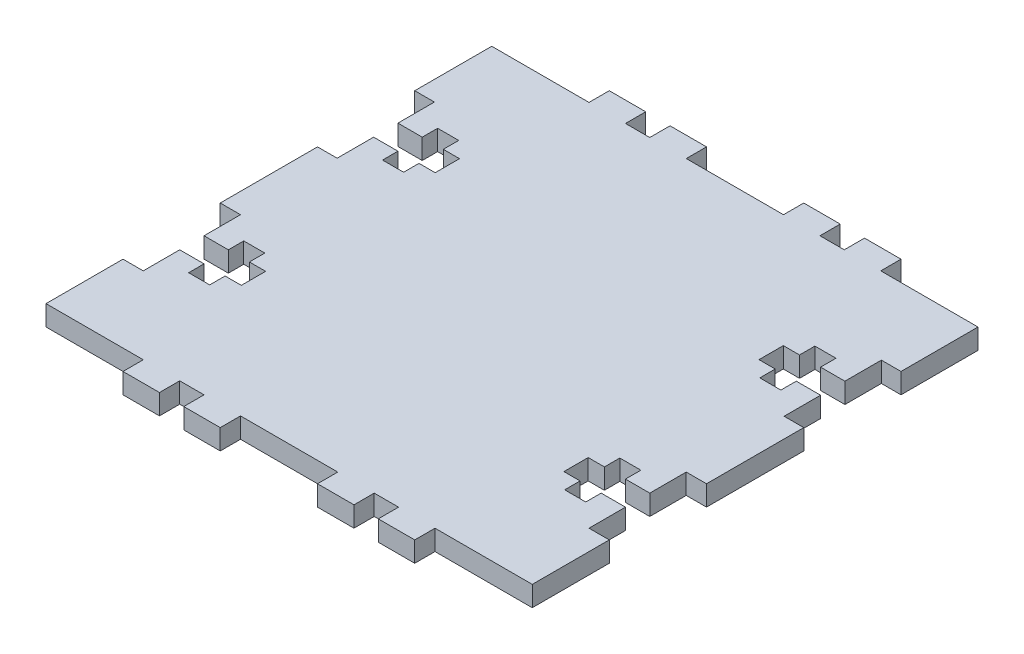
SolidWorks part; units mm, degrees
ref_plane "Front Plane" through (0, 0, 0) normal (0, 0, 1) x (1, 0, 0)
ref_plane "Top Plane" through (0, 0, 0) normal (0, 1, 0) x (1, 0, 0)
ref_plane "Right Plane" through (0, 0, 0) normal (1, 0, 0) x (0, 0, -1)
sketch "Sketch1" plane through (0, 0, 0) normal (0, 1, 0) x (1, 0, 0)
  line L0 (-38.1, 38.1) -> (38.1, -38.1) construction
  line L1 (-38.1, 38.1) -> (38.1, 38.1) construction
  line L2 (-38.1, 38.1) -> (-38.1, -38.1) construction
  line L3 (-38.1, -38.1) -> (38.1, -38.1) construction
  line L4 (38.1, 38.1) -> (38.1, -38.1) construction
  line L5 (15.24, 38.1) -> (15.24, 36.5125) construction
  line L6 (34.925, 34.925) -> (34.925, -34.925) construction
  line L7 (-34.925, -34.925) -> (34.925, -34.925) construction
  line L8 (-27.813, -13.335) -> (-25.273, -13.335)
  line L9 (-22.86, 36.5125) -> (-7.62, 36.5125) construction
  line L10 (-34.925, 34.925) -> (-22.86, 34.925)
  line L11 (-22.86, 34.925) -> (-22.86, 38.1)
  line L12 (-22.86, 38.1) -> (-17.145, 38.1)
  line L13 (-7.62, 38.1) -> (-7.62, 34.925)
  line L14 (-7.62, 34.925) -> (7.62, 34.925)
  line L15 (7.62, 34.925) -> (7.62, 38.1)
  line L16 (13.335, 38.1) -> (7.62, 38.1)
  line L17 (22.86, 38.1) -> (22.86, 34.925)
  line L18 (22.86, 34.925) -> (34.925, 34.925)
  line L19 (7.62, 36.5125) -> (22.86, 36.5125) construction
  line L20 (-15.24, -38.1) -> (-15.24, -36.5125) construction
  line L21 (-15.24, 38.1) -> (-15.24, 36.5125) construction
  line L22 (7.62, -36.5125) -> (22.86, -36.5125) construction
  line L23 (-22.86, -36.5125) -> (-7.62, -36.5125) construction
  line L24 (15.24, -38.1) -> (15.24, -36.5125) construction
  line L25 (22.86, -34.925) -> (34.925, -34.925)
  line L26 (22.86, -38.1) -> (22.86, -34.925)
  line L27 (22.86, -38.1) -> (17.145, -38.1)
  line L28 (7.62, -34.925) -> (7.62, -38.1)
  line L29 (-7.62, -34.925) -> (7.62, -34.925)
  line L30 (-34.925, 34.925) -> (34.925, 34.925) construction
  line L31 (-7.62, -38.1) -> (-7.62, -34.925)
  line L32 (17.145, -34.925) -> (17.145, -38.1)
  line L33 (-22.86, -34.925) -> (-22.86, -38.1)
  line L34 (-34.925, -34.925) -> (-22.86, -34.925)
  line L35 (-35.0215, 0) -> (34.925, 0) construction
  line L36 (-27.9095, 17.145) -> (-25.3695, 17.145)
  line L37 (-35.0215, 13.335) -> (-35.0215, 17.145) construction
  line L38 (-35.0215, 22.86) -> (-35.0215, 7.62) construction
  line L39 (-35.0215, 13.335) -> (-31.2115, 13.335)
  line L40 (-31.2115, 13.335) -> (-31.2115, 10.922)
  line L41 (-31.2115, 10.922) -> (-27.9095, 10.922)
  line L42 (-27.9095, 10.922) -> (-27.9095, 13.335)
  line L43 (-27.9095, 13.335) -> (-25.3695, 13.335)
  line L44 (-25.3695, 13.335) -> (-25.3695, 17.145)
  line L45 (-35.0215, 15.24) -> (-25.3695, 15.24) construction
  line L46 (-27.9095, 19.558) -> (-27.9095, 17.145)
  line L47 (-31.2115, 17.145) -> (-31.2115, 19.558)
  line L48 (-31.2115, 19.558) -> (-27.9095, 19.558)
  line L49 (-35.0215, 17.145) -> (-31.2115, 17.145)
  line L50 (-34.925, 34.925) -> (-38.1, 34.925)
  line L51 (34.925, 34.925) -> (38.1, 34.925)
  line L52 (-38.1, 34.925) -> (-38.1, 22.86)
  line L53 (-38.1, 22.86) -> (-35.0215, 22.86)
  line L54 (-35.0215, 22.86) -> (-35.0215, 7.62) construction
  line L55 (-35.0215, 7.62) -> (-38.1, 7.62)
  line L56 (-38.1, 7.62) -> (-38.1, -7.62)
  line L57 (-38.1, -7.62) -> (-34.925, -7.62)
  line L58 (-34.925, -7.62) -> (-34.925, -22.86) construction
  line L59 (-34.925, -22.86) -> (-38.1, -22.86)
  line L60 (-38.1, -22.86) -> (-38.1, -34.925)
  line L61 (-38.1, -34.925) -> (-34.925, -34.925)
  line L62 (-34.925, -17.145) -> (-34.925, -13.335) construction
  line L63 (-34.925, 34.925) -> (-34.925, -34.925) construction
  line L64 (-34.925, -17.145) -> (-31.115, -17.145)
  line L65 (-31.115, -17.145) -> (-31.115, -19.558)
  line L66 (-31.115, -19.558) -> (-27.813, -19.558)
  line L67 (-27.813, -19.558) -> (-27.813, -17.145)
  line L68 (-27.813, -17.145) -> (-25.273, -17.145)
  line L69 (-25.273, -17.145) -> (-25.273, -13.335)
  line L70 (-34.925, -15.24) -> (-25.273, -15.24) construction
  line L71 (-27.813, -10.922) -> (-27.813, -13.335)
  line L72 (-31.115, -13.335) -> (-31.115, -10.922)
  line L73 (-31.115, -10.922) -> (-27.813, -10.922)
  line L74 (-34.925, -13.335) -> (-31.115, -13.335)
  line L75 (-34.925, -7.62) -> (-34.925, -13.335)
  line L76 (-34.925, -17.145) -> (-34.925, -22.86)
  line L77 (-35.0215, 22.86) -> (-35.0215, 17.145)
  line L78 (-35.0215, 13.335) -> (-35.0215, 7.62)
  line L79 (0, 38.1) -> (0, -34.925) construction
  line L80 (38.1, 34.925) -> (38.1, 22.86)
  line L81 (38.1, -22.86) -> (38.1, -34.925)
  line L82 (34.925, -22.86) -> (38.1, -22.86)
  line L83 (38.1, -7.62) -> (34.925, -7.62)
  line L84 (38.1, 7.62) -> (38.1, -7.62)
  line L85 (35.0215, 7.62) -> (38.1, 7.62)
  line L86 (38.1, 22.86) -> (35.0215, 22.86)
  line L87 (34.925, -15.24) -> (25.273, -15.24) construction
  line L88 (34.925, -17.145) -> (34.925, -13.335) construction
  line L89 (34.925, -7.62) -> (34.925, -22.86) construction
  line L90 (35.0215, 22.86) -> (35.0215, 7.62) construction
  line L91 (35.0215, 15.24) -> (25.3695, 15.24) construction
  line L92 (35.0215, 22.86) -> (35.0215, 7.62) construction
  line L93 (35.0215, 13.335) -> (35.0215, 17.145) construction
  line L94 (35.0215, 13.335) -> (35.0215, 7.62)
  line L95 (35.0215, 22.86) -> (35.0215, 17.145)
  line L96 (34.925, -17.145) -> (34.925, -22.86)
  line L97 (34.925, -7.62) -> (34.925, -13.335)
  line L98 (34.925, -13.335) -> (31.115, -13.335)
  line L99 (31.115, -10.922) -> (27.813, -10.922)
  line L100 (31.115, -13.335) -> (31.115, -10.922)
  line L101 (27.813, -10.922) -> (27.813, -13.335)
  line L102 (25.273, -17.145) -> (25.273, -13.335)
  line L103 (27.813, -17.145) -> (25.273, -17.145)
  line L104 (27.813, -19.558) -> (27.813, -17.145)
  line L105 (31.115, -19.558) -> (27.813, -19.558)
  line L106 (31.115, -17.145) -> (31.115, -19.558)
  line L107 (34.925, -17.145) -> (31.115, -17.145)
  line L108 (35.0215, 17.145) -> (31.2115, 17.145)
  line L109 (31.2115, 19.558) -> (27.9095, 19.558)
  line L110 (31.2115, 17.145) -> (31.2115, 19.558)
  line L111 (27.9095, 19.558) -> (27.9095, 17.145)
  line L112 (25.3695, 13.335) -> (25.3695, 17.145)
  line L113 (27.9095, 13.335) -> (25.3695, 13.335)
  line L114 (27.9095, 10.922) -> (27.9095, 13.335)
  line L115 (31.2115, 10.922) -> (27.9095, 10.922)
  line L116 (31.2115, 13.335) -> (31.2115, 10.922)
  line L117 (35.0215, 13.335) -> (31.2115, 13.335)
  line L118 (27.9095, 17.145) -> (25.3695, 17.145)
  line L119 (27.813, -13.335) -> (25.273, -13.335)
  line L120 (34.925, -34.925) -> (38.1, -34.925)
  line L121 (-13.335, 38.1) -> (-7.62, 38.1)
  line L122 (-17.145, 34.925) -> (-13.335, 34.925)
  line L123 (-17.145, 34.925) -> (-17.145, 38.1)
  line L124 (-17.145, 38.1) -> (-13.335, 38.1) construction
  line L125 (-13.335, 34.925) -> (-13.335, 38.1)
  line L126 (13.335, 34.925) -> (13.335, 38.1)
  line L127 (17.145, 34.925) -> (13.335, 34.925)
  line L128 (17.145, 34.925) -> (17.145, 38.1)
  line L129 (22.86, 38.1) -> (17.145, 38.1)
  line L130 (17.145, -34.925) -> (13.335, -34.925)
  line L131 (13.335, -38.1) -> (7.62, -38.1)
  line L132 (13.335, -34.925) -> (13.335, -38.1)
  line L133 (-13.335, -38.1) -> (-7.62, -38.1)
  line L134 (-13.335, -34.925) -> (-13.335, -38.1)
  line L135 (-17.145, -34.925) -> (-13.335, -34.925)
  line L136 (-17.145, -34.925) -> (-17.145, -38.1)
  line L137 (-22.86, -38.1) -> (-17.145, -38.1)
  point P4 (0, 0)
  point P43 (-35.0215, 15.24)
  dimension "D6" = 3.175
  dimension "D1" = 3.175
  dimension "D2" = 76.2
  dimension "D3" = 76.2
  dimension "D4" = 15.24
  dimension "D5" = 12.065
  dimension "D7" = 3.302
  dimension "D8" = 1.905
  dimension "D9" = 3.81
  dimension "D10" = 2.54
  dimension "D11" = 3.81
  dimension "D12" = 15.24
  dimension "D13" = 3.302
  dimension "D14" = 1.905
  dimension "D15" = 3.81
  dimension "D16" = 2.54
  dimension "D17" = 4.318
extrude "Boss-Extrude1" add sketch "Sketch1" along normal blind 3.175
